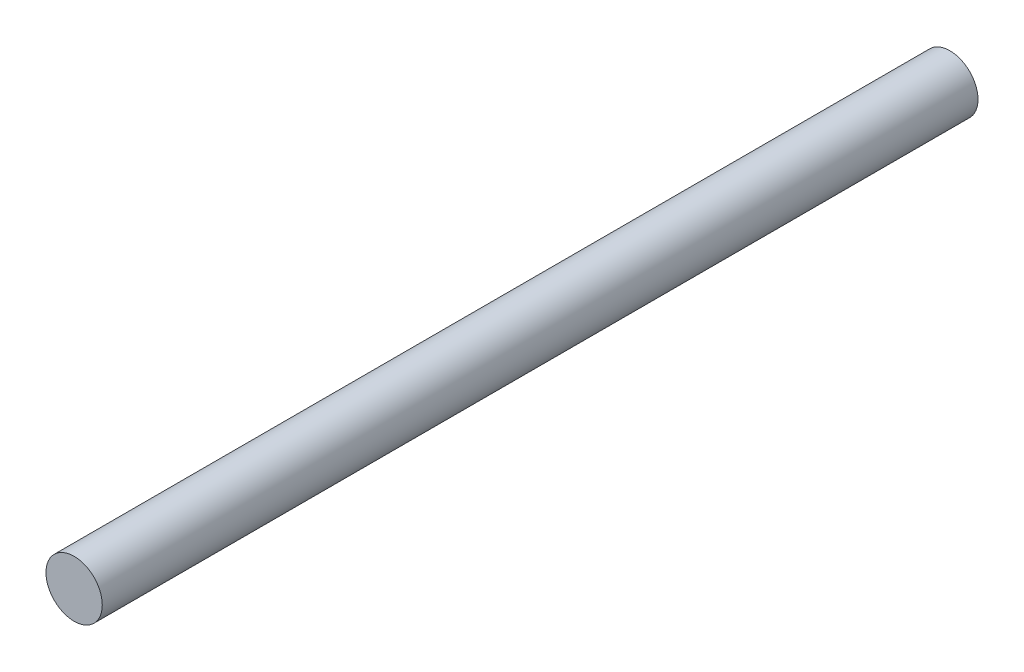
SolidWorks part; units mm, degrees
ref_plane "Front Plane" through (0, 0, 0) normal (0, 0, 1) x (1, 0, 0)
ref_plane "Top Plane" through (0, 0, 0) normal (0, 1, 0) x (1, 0, 0)
ref_plane "Right Plane" through (0, 0, 0) normal (1, 0, 0) x (0, 0, -1)
sketch "Sketch1" plane through (0, 0, 0) normal (0, 0, 1) x (1, 0, 0)
  circle A0 centre (0, 0) radius 8.89
  dimension "D1" = 17.78
extrude "Boss-Extrude1" add sketch "Sketch1" along normal blind 143.2 and the other way blind 133.2
